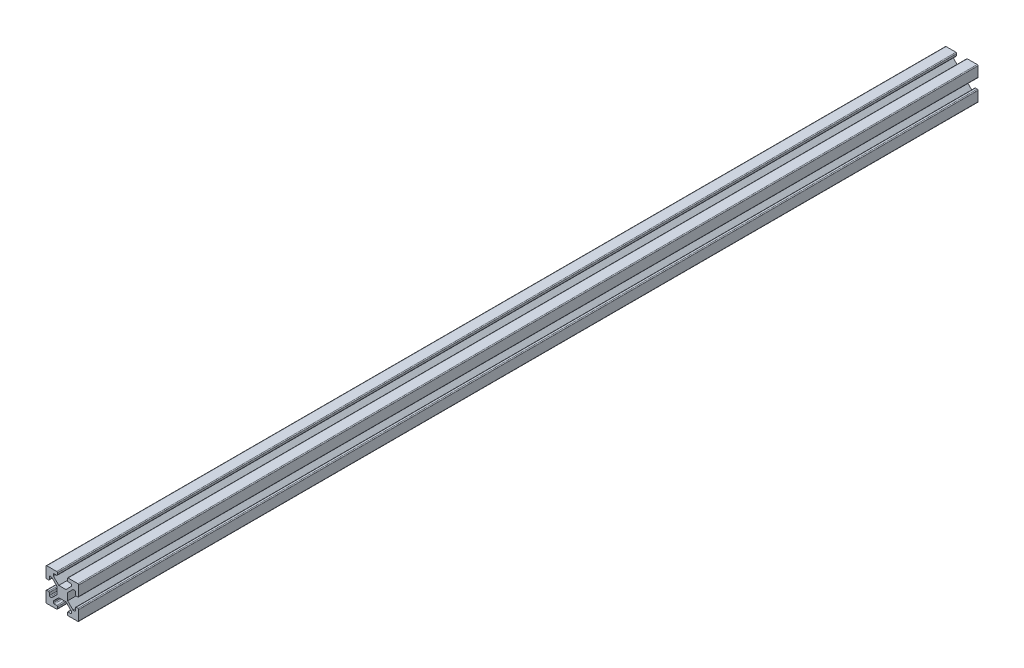
SolidWorks part; units mm, degrees
material "3.1645 (EN AW-2007)"
ref_plane "Front" through (0, 0, 0) normal (0, 0, 1) x (1, 0, 0)
ref_plane "Top" through (0, 0, 0) normal (0, 1, 0) x (1, 0, 0)
ref_plane "Right" through (0, 0, 0) normal (1, 0, 0) x (0, 0, -1)
sketch "草图1" plane through (0, 0, 0) normal (0, 0, 1) x (1, 0, 0)
  line L0 (6.5, 0) -> (0.5, 0)
  line L1 (20, -0.5) -> (20, -6.5)
  line L2 (19.5, -20) -> (13.5, -20)
  line L3 (20, -13.5) -> (20, -19.5)
  line L4 (13, -19.5) -> (13, -18.5)
  line L5 (13.5, -18) -> (15, -18)
  line L6 (15.5, -17.5) -> (15.5, -16.7791)
  line L7 (19.5, -7) -> (18.5, -7)
  line L8 (10, 0) -> (10, -26.2948) construction
  line L9 (18, -6.5) -> (18, -5)
  line L10 (17.5, -4.5) -> (16.7791, -4.5)
  line L11 (17.5, -15.5) -> (16.7791, -15.5)
  line L12 (18, -13.5) -> (18, -15)
  line L13 (19.5, -13) -> (18.5, -13)
  line L15 (0, -10) -> (20, -10) construction
  line L23 (4.5, -17.5) -> (4.5, -16.7791)
  line L24 (6.5, -18) -> (5, -18)
  line L25 (7, -19.5) -> (7, -18.5)
  line L27 (0.5, -20) -> (6.5, -20)
  line L29 (10, -20) -> (10, 6.2948) construction
  line L33 (0.5, -13) -> (1.5, -13)
  line L34 (2, -13.5) -> (2, -15)
  line L35 (2.5, -15.5) -> (3.2209, -15.5)
  line L36 (2.5, -4.5) -> (3.2209, -4.5)
  line L37 (2, -6.5) -> (2, -5)
  line L38 (0.5, -7) -> (1.5, -7)
  line L40 (7, -0.5) -> (7, -1.5)
  line L41 (6.5, -2) -> (5, -2)
  line L42 (4.5, -2.5) -> (4.5, -3.2209)
  line L43 (3.5745, -4.6464) -> (6.7416, -7.8136)
  line L44 (6.7416, -7.8136) -> (6.7416, -12.1864)
  line L45 (15.5, -2.5) -> (15.5, -3.2209)
  line L46 (13.5, -2) -> (15, -2)
  line L47 (13, -0.5) -> (13, -1.5)
  line L48 (19.5, 0) -> (13.5, 0)
  line L50 (10.3536, -10.3536) -> (20, -20) construction
  line L51 (4.6464, -3.5745) -> (7.8136, -6.7416)
  line L52 (7.8136, -6.7416) -> (12.1864, -6.7416)
  line L53 (0, -20) -> (9.6464, -10.3536) construction
  line L54 (15.3536, -3.5745) -> (12.1864, -6.7416)
  line L55 (13.2584, -7.8136) -> (13.2584, -12.1864)
  line L56 (16.4255, -4.6464) -> (13.2584, -7.8136)
  line L57 (10, 0) -> (10, -26.2948) construction
  line L58 (10, -20) -> (10, 6.2948) construction
  line L59 (16.4255, -15.3536) -> (13.2584, -12.1864)
  line L60 (15.3536, -16.4255) -> (12.3328, -13.4048)
  line L61 (8.0207, -13.2584) -> (11.9793, -13.2584)
  line L62 (4.6464, -16.4255) -> (7.6672, -13.4048)
  line L63 (3.5745, -15.3536) -> (6.7416, -12.1864)
  line L64 (0, -6.5) -> (0, -0.5)
  line L66 (0, -13.5) -> (0, -19.5)
  arc A0 (19.5, -7) -> (20, -6.5) centre (19.5, -6.5) ccw
  arc A1 (4.6464, -16.4255) -> (4.5, -16.7791) centre (5, -16.7791) ccw
  arc A2 (8.0207, -13.2584) -> (7.6672, -13.4048) centre (8.0207, -13.7584) ccw
  arc A3 (12.3328, -13.4048) -> (11.9793, -13.2584) centre (11.9793, -13.7584) ccw
  arc A4 (16.4255, -15.3536) -> (16.7791, -15.5) centre (16.7791, -15) ccw
  arc A5 (16.4255, -4.6464) -> (16.7791, -4.5) centre (16.7791, -5) cw
  arc A6 (15.3536, -16.4255) -> (15.5, -16.7791) centre (15, -16.7791) cw
  arc A7 (10.3536, -10.3536) -> (9.6464, -10.3536) centre (10, -10.7071) ccw construction
  arc A8 (15.3536, -3.5745) -> (15.5, -3.2209) centre (15, -3.2209) ccw
  arc A9 (3.5745, -15.3536) -> (3.2209, -15.5) centre (3.2209, -15) cw
  arc A10 (3.5745, -4.6464) -> (3.2209, -4.5) centre (3.2209, -5) ccw
  arc A11 (0.5, -7) -> (0, -6.5) centre (0.5, -6.5) cw
  arc A12 (2, -6.5) -> (1.5, -7) centre (1.5, -6.5) cw
  arc A13 (4.6464, -3.5745) -> (4.5, -3.2209) centre (5, -3.2209) cw
  arc A14 (2.5, -4.5) -> (2, -5) centre (2.5, -5) ccw
  arc A15 (2, -15) -> (2.5, -15.5) centre (2.5, -15) ccw
  arc A16 (1.5, -13) -> (2, -13.5) centre (1.5, -13.5) cw
  arc A17 (0.5, -13) -> (0, -13.5) centre (0.5, -13.5) ccw
  arc A18 (19.5, -13) -> (20, -13.5) centre (19.5, -13.5) cw
  arc A19 (13.5, 0) -> (13, -0.5) centre (13.5, -0.5) ccw
  arc A20 (13, -1.5) -> (13.5, -2) centre (13.5, -1.5) ccw
  arc A21 (15, -2) -> (15.5, -2.5) centre (15, -2.5) cw
  arc A22 (18, -13.5) -> (18.5, -13) centre (18.5, -13.5) cw
  arc A23 (4.5, -2.5) -> (5, -2) centre (5, -2.5) cw
  arc A24 (6.5, -2) -> (7, -1.5) centre (6.5, -1.5) ccw
  arc A25 (7, -0.5) -> (6.5, 0) centre (6.5, -0.5) ccw
  arc A26 (6.5, -18) -> (7, -18.5) centre (6.5, -18.5) cw
  arc A27 (4.5, -17.5) -> (5, -18) centre (5, -17.5) ccw
  arc A28 (17.5, -15.5) -> (18, -15) centre (17.5, -15) ccw
  arc A29 (15, -18) -> (15.5, -17.5) centre (15, -17.5) ccw
  arc A30 (13, -18.5) -> (13.5, -18) centre (13.5, -18.5) cw
  arc A31 (18, -5) -> (17.5, -4.5) centre (17.5, -5) ccw
  arc A32 (18.5, -7) -> (18, -6.5) centre (18.5, -6.5) cw
  arc A33 (19.5, 0) -> (20, -0.5) centre (19.5, -0.5) cw
  arc A34 (0.5, 0) -> (0, -0.5) centre (0.5, -0.5) ccw
  arc A35 (7, -19.5) -> (6.5, -20) centre (6.5, -19.5) cw
  arc A36 (13.5, -20) -> (13, -19.5) centre (13.5, -19.5) cw
  arc A37 (0.5, -20) -> (0, -19.5) centre (0.5, -19.5) cw
  arc A38 (20, -19.5) -> (19.5, -20) centre (19.5, -19.5) cw
  point P28 (4.5, -16.572)
  point P50 (10, -6.7416)
  point P56 (13.2584, -10)
  point P61 (6.7416, -10)
  point P62 (10, -13.2584)
  point P63 (7.8136, -13.2584)
  point P66 (12.1864, -13.2584)
  point P69 (16.572, -15.5)
  point P72 (16.572, -4.5)
  point P75 (15.5, -16.572)
  point P78 (10, -10)
  point P81 (15.5, -3.428)
  point P84 (3.428, -15.5)
  point P87 (3.428, -4.5)
  point P94 (4.5, -3.428)
  point P107 (13, 0)
  point P110 (13, -2)
  point P113 (15.5, -2)
  point P118 (4.5, -2)
  point P121 (7, -2)
  point P124 (7, 0)
  point P127 (7, -18)
  point P130 (4.5, -18)
  point P135 (15.5, -18)
  point P138 (13, -18)
  point P145 (20, 0)
  point P148 (0, 0)
  point P151 (7, -20)
  point P154 (13, -20)
  dimension "D1" = 6.7416
  dimension "D2" = 6
  dimension "D3" = 2
extrude "凸台-拉伸1" add sketch "草图1" along normal blind 550
